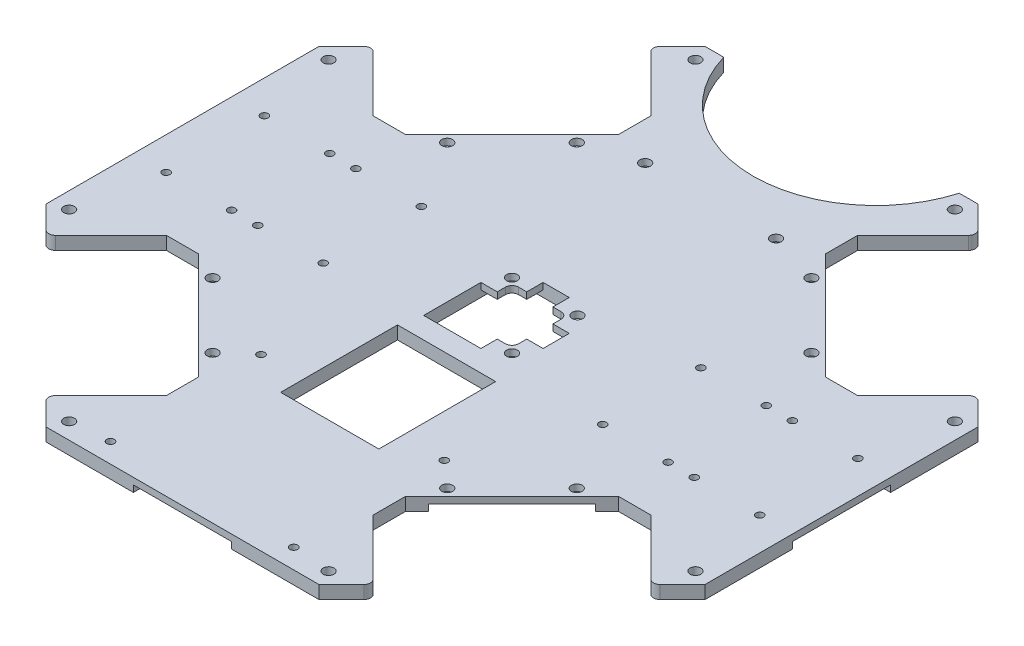
SolidWorks part; units mm, degrees
ref_plane "Front Plane" through (0, 0, 0) normal (0, 0, 1) x (1, 0, 0)
ref_plane "Top Plane" through (0, 0, 0) normal (0, 1, 0) x (1, 0, 0)
ref_plane "Right Plane" through (0, 0, 0) normal (1, 0, 0) x (0, 0, -1)
sketch "Sketch1" plane through (0, 0, 0) normal (0, 1, 0) x (1, 0, 0)
  line L1 (-41.7125, 100.7029) -> (-100.7029, 41.7125)
  line L2 (-100.7029, 41.7125) -> (-100.7029, -41.7125)
  line L3 (-100.7029, -41.7125) -> (-41.7125, -100.7029)
  line L4 (-41.7125, -100.7029) -> (41.7125, -100.7029)
  line L5 (41.7125, -100.7029) -> (100.7029, -41.7125)
  line L6 (100.7029, -41.7125) -> (100.7029, 41.7125)
  line L7 (100.7029, 41.7125) -> (41.7125, 100.7029)
  line L8 (41.7125, 100.7029) -> (-41.7125, 100.7029)
  circle A0 centre (0, 0) radius 100.7029 construction
  circle A1 centre (0, 0) radius 109 construction
  dimension "D1" = 218
extrude "Boss-Extrude1" add sketch "Sketch1" along normal blind 4
sketch "Sketch2" plane through (0, 4, 0) normal (0, 1, 0) x (1, 0, 0)
  line L5 (-92.4209, 49.9945) -> (-49.9945, 92.4209)
  line L6 (-92.4209, 49.9945) -> (-69.0864, 26.66)
  line L7 (-49.9945, 92.4209) -> (-26.66, 69.0864)
  line L8 (-69.0864, 26.66) -> (-26.66, 69.0864)
  line L9 (-41.7125, 100.7029) -> (-100.7029, 41.7125) construction
  line L10 (0, 0) -> (-71.2077, 71.2077) construction
  line L11 (100.7029, 41.7125) -> (41.7125, 100.7029) construction
  line L12 (49.9945, 92.4209) -> (92.4209, 49.9945)
  line L13 (49.9945, 92.4209) -> (26.66, 69.0864)
  line L14 (26.66, 69.0864) -> (69.0864, 26.66)
  line L15 (92.4209, 49.9945) -> (69.0864, 26.66)
  line L16 (92.4209, -49.9945) -> (49.9945, -92.4209)
  line L17 (92.4209, -49.9945) -> (69.0864, -26.66)
  line L18 (69.0864, -26.66) -> (26.66, -69.0864)
  line L19 (49.9945, -92.4209) -> (26.66, -69.0864)
  line L20 (-49.9945, -92.4209) -> (-92.4209, -49.9945)
  line L21 (-49.9945, -92.4209) -> (-26.66, -69.0864)
  line L22 (-26.66, -69.0864) -> (-69.0864, -26.66)
  line L23 (-92.4209, -49.9945) -> (-69.0864, -26.66)
  circle A0 centre (-55.6513, 35.8523) radius 1.65
  circle A1 centre (-35.8523, 55.6513) radius 1.65
  circle A2 centre (55.6513, 35.8523) radius 1.65
  circle A3 centre (35.8523, 55.6513) radius 1.65
  circle A4 centre (35.8523, -55.6513) radius 1.65
  circle A5 centre (55.6513, -35.8523) radius 1.65
  circle A6 centre (-55.6513, -35.8523) radius 1.65
  circle A7 centre (-35.8523, -55.6513) radius 1.65
  point P42 (0, 0)
  dimension "D7" = 3.3
  dimension "D8" = 3.3
  dimension "D1" = 60
  dimension "D2" = 33
  dimension "D3" = 3
  dimension "D4" = 3
  dimension "D5" = 28
  dimension "D6" = 14
  dimension "D10" = 71.7047
  dimension "D11" = 67.7029
  dimension "D9" = 4
extrude "Cut-Extrude1" cut sketch "Sketch2" against normal up to next
sketch "Sketch3" plane through (0, 4, 0) normal (0, 1, 0) x (1, 0, 0)
  line L0 (0, 0) -> (0, 50000) construction
  line L1 (-1015.9137, 73.7029) -> (48984.0863, 73.7029) construction
  line L2 (41.7125, 100.7029) -> (-41.7125, 100.7029) construction
  circle A0 centre (0, 111.2029) radius 37.5
  dimension "D1" = 75
  dimension "D2" = 27
extrude "Cut-Extrude2" cut sketch "Sketch3" against normal up to next
chamfer "Chamfer2" distance 7 angle 45 8 edges at (-69.0864, 2, 26.66) (-26.66, 2, 69.0864) (26.66, 2, 69.0864) (69.0864, 2, 26.66) (69.0864, 2, -26.66) (26.66, 2, -69.0864) (-69.0864, 2, -26.66) (-26.66, 2, -69.0864)
sketch "Sketch4" plane through (0, 4, 0) normal (0, 1, 0) x (1, 0, 0)
  line L0 (-36, 100.7029) -> (-41.7125, 100.7029) construction
  line L1 (-41.7125, 100.7029) -> (-49.9945, 92.4209) construction
  line L2 (41.7125, 100.7029) -> (36, 100.7029) construction
  line L3 (49.9945, 92.4209) -> (41.7125, 100.7029) construction
  circle A0 centre (-39.6414, 95.7029) radius 1.65
  circle A1 centre (39.6414, 95.7029) radius 1.65
  circle A2 centre (95.7029, 39.6414) radius 1.65
  circle A3 centre (95.7029, -39.6414) radius 1.65
  circle A4 centre (39.6414, -95.7029) radius 1.65
  circle A5 centre (-39.6414, -95.7029) radius 1.65
  circle A6 centre (-95.7029, -39.6414) radius 1.65
  circle A7 centre (-95.7029, 39.6414) radius 1.65
  point P22 (0, 0)
  dimension "D3" = 3.3
  dimension "D1" = 5
  dimension "D2" = 5
  dimension "D5" = 5
  dimension "D6" = 5
  dimension "D4" = 8
extrude "Cut-Extrude3" cut sketch "Sketch4" against normal up to next
sketch "Sketch5" plane through (0, 4, 0) normal (0, 1, 0) x (1, 0, 0)
  line L0 (-1000, 0) -> (49000, 0) construction
  line L1 (0, -1000) -> (0, 49000) construction
  line L2 (-62.7029, 15) -> (-42.7029, 15) construction
  line L3 (-90.7029, 15) -> (-70.7029, 15) construction
  line L4 (-90.7029, 15) -> (-90.7029, -15) construction
  line L5 (-90.7029, -15) -> (-70.7029, -15) construction
  line L6 (-70.7029, 15) -> (-70.7029, -15) construction
  line L7 (-62.7029, 15) -> (-62.7029, -15) construction
  line L8 (-62.7029, -15) -> (-42.7029, -15) construction
  line L9 (-42.7029, 15) -> (-42.7029, -15) construction
  line L10 (-100.7029, 41.7125) -> (-100.7029, -41.7125) construction
  line L11 (42.7029, 15) -> (42.7029, -15) construction
  line L12 (62.7029, -15) -> (42.7029, -15) construction
  line L13 (62.7029, 15) -> (62.7029, -15) construction
  line L14 (70.7029, 15) -> (70.7029, -15) construction
  line L15 (90.7029, -15) -> (70.7029, -15) construction
  line L16 (90.7029, 15) -> (90.7029, -15) construction
  line L17 (90.7029, 15) -> (70.7029, 15) construction
  line L18 (62.7029, 15) -> (42.7029, 15) construction
  circle A0 centre (-90.7029, 15) radius 1.15
  circle A1 centre (-70.7029, 15) radius 1.15
  circle A2 centre (-62.7029, 15) radius 1.15
  circle A3 centre (-42.7029, 15) radius 1.15
  circle A4 centre (-42.7029, -15) radius 1.15
  circle A5 centre (-62.7029, -15) radius 1.15
  circle A6 centre (-70.7029, -15) radius 1.15
  circle A7 centre (-90.7029, -15) radius 1.15
  circle A8 centre (90.7029, -15) radius 1.15
  circle A9 centre (70.7029, -15) radius 1.15
  circle A10 centre (62.7029, -15) radius 1.15
  circle A11 centre (42.7029, -15) radius 1.15
  circle A12 centre (42.7029, 15) radius 1.15
  circle A13 centre (62.7029, 15) radius 1.15
  circle A14 centre (70.7029, 15) radius 1.15
  circle A15 centre (90.7029, 15) radius 1.15
  dimension "D9" = 2.3
  dimension "D10" = 2.3
  dimension "D11" = 2.3
  dimension "D12" = 2.3
  dimension "D13" = 2.3
  dimension "D14" = 2.3
  dimension "D15" = 2.3
  dimension "D16" = 2.3
  dimension "D1" = 20
  dimension "D2" = 30
  dimension "D3" = 15
  dimension "D4" = 20
  dimension "D5" = 30
  dimension "D6" = 15
  dimension "D7" = 8
  dimension "D8" = 10
extrude "Cut-Extrude4" cut sketch "Sketch5" against normal up to next
sketch "Sketch6" plane through (0, 0, 0) normal (0, -1, 0) x (1, 0, 0)
  line L0 (0, -1000) -> (0, 49000) construction
  line L1 (-89.4616, 17.15) -> (-91.9442, 17.15)
  line L2 (-91.9442, 17.15) -> (-93.1855, 15)
  line L3 (-93.1855, 15) -> (-91.9442, 12.85)
  line L4 (-91.9442, 12.85) -> (-89.4616, 12.85)
  line L5 (-89.4616, 12.85) -> (-88.2203, 15)
  line L6 (-88.2203, 15) -> (-89.4616, 17.15)
  line L7 (-73.1855, 15) -> (-71.9442, 12.85)
  line L8 (-71.9442, 12.85) -> (-69.4616, 12.85)
  line L9 (-69.4616, 12.85) -> (-68.2203, 15)
  line L10 (-68.2203, 15) -> (-69.4616, 17.15)
  line L11 (-69.4616, 17.15) -> (-71.9442, 17.15)
  line L12 (-71.9442, 17.15) -> (-73.1855, 15)
  line L13 (-63.9442, 17.15) -> (-65.1855, 15)
  line L14 (-65.1855, 15) -> (-63.9442, 12.85)
  line L15 (-63.9442, 12.85) -> (-61.4616, 12.85)
  line L16 (-61.4616, 12.85) -> (-60.2203, 15)
  line L17 (-60.2203, 15) -> (-61.4616, 17.15)
  line L18 (-61.4616, 17.15) -> (-63.9442, 17.15)
  line L19 (-43.9442, 17.15) -> (-45.1855, 15)
  line L20 (-45.1855, 15) -> (-43.9442, 12.85)
  line L21 (-43.9442, 12.85) -> (-41.4616, 12.85)
  line L22 (-41.4616, 12.85) -> (-40.2203, 15)
  line L23 (-40.2203, 15) -> (-41.4616, 17.15)
  line L24 (-41.4616, 17.15) -> (-43.9442, 17.15)
  line L25 (-91.9442, -12.85) -> (-93.1855, -15)
  line L26 (-93.1855, -15) -> (-91.9442, -17.15)
  line L27 (-91.9442, -17.15) -> (-89.4616, -17.15)
  line L28 (-89.4616, -17.15) -> (-88.2203, -15)
  line L29 (-88.2203, -15) -> (-89.4616, -12.85)
  line L30 (-89.4616, -12.85) -> (-91.9442, -12.85)
  line L31 (-73.1855, -15) -> (-71.9442, -17.15)
  line L32 (-71.9442, -17.15) -> (-69.4616, -17.15)
  line L33 (-69.4616, -17.15) -> (-68.2203, -15)
  line L34 (-68.2203, -15) -> (-69.4616, -12.85)
  line L35 (-69.4616, -12.85) -> (-71.9442, -12.85)
  line L36 (-71.9442, -12.85) -> (-73.1855, -15)
  line L37 (-63.9442, -12.85) -> (-65.1855, -15)
  line L38 (-65.1855, -15) -> (-63.9442, -17.15)
  line L39 (-63.9442, -17.15) -> (-61.4616, -17.15)
  line L40 (-61.4616, -17.15) -> (-60.2203, -15)
  line L41 (-60.2203, -15) -> (-61.4616, -12.85)
  line L42 (-61.4616, -12.85) -> (-63.9442, -12.85)
  line L43 (-43.9442, -12.85) -> (-45.1855, -15)
  line L44 (-45.1855, -15) -> (-43.9442, -17.15)
  line L45 (-43.9442, -17.15) -> (-41.4616, -17.15)
  line L46 (-41.4616, -17.15) -> (-40.2203, -15)
  line L47 (-40.2203, -15) -> (-41.4616, -12.85)
  line L48 (-41.4616, -12.85) -> (-43.9442, -12.85)
  line L49 (41.4616, -12.85) -> (43.9442, -12.85)
  line L50 (40.2203, -15) -> (41.4616, -12.85)
  line L51 (41.4616, -17.15) -> (40.2203, -15)
  line L52 (43.9442, -17.15) -> (41.4616, -17.15)
  line L53 (45.1855, -15) -> (43.9442, -17.15)
  line L54 (43.9442, -12.85) -> (45.1855, -15)
  line L55 (61.4616, -12.85) -> (63.9442, -12.85)
  line L56 (60.2203, -15) -> (61.4616, -12.85)
  line L57 (61.4616, -17.15) -> (60.2203, -15)
  line L58 (63.9442, -17.15) -> (61.4616, -17.15)
  line L59 (65.1855, -15) -> (63.9442, -17.15)
  line L60 (63.9442, -12.85) -> (65.1855, -15)
  line L61 (71.9442, -12.85) -> (73.1855, -15)
  line L62 (69.4616, -12.85) -> (71.9442, -12.85)
  line L63 (68.2203, -15) -> (69.4616, -12.85)
  line L64 (69.4616, -17.15) -> (68.2203, -15)
  line L65 (71.9442, -17.15) -> (69.4616, -17.15)
  line L66 (73.1855, -15) -> (71.9442, -17.15)
  line L67 (89.4616, -12.85) -> (91.9442, -12.85)
  line L68 (88.2203, -15) -> (89.4616, -12.85)
  line L69 (89.4616, -17.15) -> (88.2203, -15)
  line L70 (91.9442, -17.15) -> (89.4616, -17.15)
  line L71 (93.1855, -15) -> (91.9442, -17.15)
  line L72 (91.9442, -12.85) -> (93.1855, -15)
  line L73 (41.4616, 17.15) -> (43.9442, 17.15)
  line L74 (40.2203, 15) -> (41.4616, 17.15)
  line L75 (41.4616, 12.85) -> (40.2203, 15)
  line L76 (43.9442, 12.85) -> (41.4616, 12.85)
  line L77 (45.1855, 15) -> (43.9442, 12.85)
  line L78 (43.9442, 17.15) -> (45.1855, 15)
  line L79 (61.4616, 17.15) -> (63.9442, 17.15)
  line L80 (60.2203, 15) -> (61.4616, 17.15)
  line L81 (61.4616, 12.85) -> (60.2203, 15)
  line L82 (63.9442, 12.85) -> (61.4616, 12.85)
  line L83 (65.1855, 15) -> (63.9442, 12.85)
  line L84 (63.9442, 17.15) -> (65.1855, 15)
  line L85 (71.9442, 17.15) -> (73.1855, 15)
  line L86 (69.4616, 17.15) -> (71.9442, 17.15)
  line L87 (68.2203, 15) -> (69.4616, 17.15)
  line L88 (69.4616, 12.85) -> (68.2203, 15)
  line L89 (71.9442, 12.85) -> (69.4616, 12.85)
  line L90 (73.1855, 15) -> (71.9442, 12.85)
  line L91 (88.2203, 15) -> (89.4616, 17.15)
  line L92 (89.4616, 12.85) -> (88.2203, 15)
  line L93 (91.9442, 12.85) -> (89.4616, 12.85)
  line L94 (93.1855, 15) -> (91.9442, 12.85)
  line L95 (91.9442, 17.15) -> (93.1855, 15)
  line L96 (89.4616, 17.15) -> (91.9442, 17.15)
  circle A0 centre (-90.7029, 15) radius 2.15 construction
  circle A1 centre (-70.7029, 15) radius 2.15 construction
  circle A2 centre (-62.7029, 15) radius 2.15 construction
  circle A3 centre (-42.7029, 15) radius 2.15 construction
  circle A4 centre (-90.7029, -15) radius 2.15 construction
  circle A5 centre (-70.7029, -15) radius 2.15 construction
  circle A6 centre (-62.7029, -15) radius 2.15 construction
  circle A7 centre (-42.7029, -15) radius 2.15 construction
  circle A8 centre (42.7029, -15) radius 2.15 construction
  circle A9 centre (62.7029, -15) radius 2.15 construction
  circle A10 centre (70.7029, -15) radius 2.15 construction
  circle A11 centre (90.7029, -15) radius 2.15 construction
  circle A12 centre (42.7029, 15) radius 2.15 construction
  circle A13 centre (62.7029, 15) radius 2.15 construction
  circle A14 centre (70.7029, 15) radius 2.15 construction
  circle A15 centre (90.7029, 15) radius 2.15 construction
  point P64 (-92.5648, -16.075)
  dimension "D1" = 4.3
  dimension "D2" = 4.3
  dimension "D3" = 4.3
  dimension "D4" = 4.3
  dimension "D5" = 4.3
  dimension "D6" = 4.3
  dimension "D7" = 4.3
  dimension "D8" = 4.3
extrude "Cut-Extrude5" cut sketch "Sketch6" against normal blind 2
sketch "Sketch7" plane through (0, 0, 0) normal (0, -1, 0) x (1, 0, 0)
  line L0 (-60.6011, -35.1452) -> (-54.9442, -40.8021)
  line L1 (-60.6011, -35.1452) -> (-50.7016, -25.2457)
  line L2 (-54.9442, -40.8021) -> (-45.0447, -30.9026)
  line L3 (-50.7016, -25.2457) -> (-45.0447, -30.9026)
  line L4 (-31.6097, -64.1366) -> (-64.1366, -31.6097) construction
  line L5 (-47.8732, -47.8732) -> (0, 0) construction
  line L6 (-40.8021, -54.9442) -> (-30.9026, -45.0447)
  line L7 (-25.2457, -50.7016) -> (-30.9026, -45.0447)
  line L8 (-35.1452, -60.6011) -> (-25.2457, -50.7016)
  line L9 (-35.1452, -60.6011) -> (-40.8021, -54.9442)
  line L10 (-35.1452, 60.6011) -> (-40.8021, 54.9442)
  line L11 (-35.1452, 60.6011) -> (-25.2457, 50.7016)
  line L12 (-25.2457, 50.7016) -> (-30.9026, 45.0447)
  line L13 (-40.8021, 54.9442) -> (-30.9026, 45.0447)
  line L14 (-54.9442, 40.8021) -> (-45.0447, 30.9026)
  line L15 (-50.7016, 25.2457) -> (-45.0447, 30.9026)
  line L16 (-60.6011, 35.1452) -> (-50.7016, 25.2457)
  line L17 (-60.6011, 35.1452) -> (-54.9442, 40.8021)
  line L18 (60.6011, 35.1452) -> (54.9442, 40.8021)
  line L19 (60.6011, 35.1452) -> (50.7016, 25.2457)
  line L20 (50.7016, 25.2457) -> (45.0447, 30.9026)
  line L21 (54.9442, 40.8021) -> (45.0447, 30.9026)
  line L22 (40.8021, 54.9442) -> (30.9026, 45.0447)
  line L23 (25.2457, 50.7016) -> (30.9026, 45.0447)
  line L24 (35.1452, 60.6011) -> (25.2457, 50.7016)
  line L25 (35.1452, 60.6011) -> (40.8021, 54.9442)
  line L26 (35.1452, -60.6011) -> (40.8021, -54.9442)
  line L27 (35.1452, -60.6011) -> (25.2457, -50.7016)
  line L28 (25.2457, -50.7016) -> (30.9026, -45.0447)
  line L29 (40.8021, -54.9442) -> (30.9026, -45.0447)
  line L30 (54.9442, -40.8021) -> (45.0447, -30.9026)
  line L31 (50.7016, -25.2457) -> (45.0447, -30.9026)
  line L32 (60.6011, -35.1452) -> (50.7016, -25.2457)
  line L33 (60.6011, -35.1452) -> (54.9442, -40.8021)
  circle A0 centre (-55.6513, -35.8523) radius 1.65 construction
  circle A1 centre (55.6513, -35.8523) radius 1.65 construction
  point P42 (0, 0)
  dimension "D1" = 14
  dimension "D2" = 8
  dimension "D3" = 4
  dimension "D5" = 53.7029
  dimension "D6" = 4
  dimension "D4" = 4
extrude "Cut-Extrude6" cut sketch "Sketch7" against normal blind 2
sketch "Sketch8" plane through (0, 4, 0) normal (0, 1, 0) x (1, 0, 0)
  line L1 (-10, -10) -> (10, -10) construction
  line L2 (-10, -10) -> (-10, 10) construction
  line L3 (-10, 10) -> (10, 10) construction
  line L4 (10, -10) -> (10, 10) construction
  line L5 (-6.5, 8.5) -> (6.5, 8.5)
  line L6 (-8.5, 6.5) -> (-8.5, -6.5)
  line L7 (-6.5, -8.5) -> (6.5, -8.5)
  line L8 (8.5, 6.5) -> (8.5, -6.5)
  circle A0 centre (-10, -10) radius 1.65
  circle A1 centre (10, -10) radius 1.65
  circle A2 centre (10, 10) radius 1.65
  circle A3 centre (-10, 10) radius 1.65
  arc A4 (-8.5, -6.5) -> (-6.5, -8.5) centre (-6.5, -6.5) ccw
  arc A5 (6.5, -8.5) -> (8.5, -6.5) centre (6.5, -6.5) ccw
  arc A6 (6.5, 8.5) -> (8.5, 6.5) centre (6.5, 6.5) cw
  arc A7 (-6.5, 8.5) -> (-8.5, 6.5) centre (-6.5, 6.5) ccw
  dimension "D5" = 3.3
  dimension "D6" = 3.3
  dimension "D7" = 3.3
  dimension "D8" = 3.3
  dimension "D13" = 2
  dimension "D1" = 20
  dimension "D2" = 20
  dimension "D3" = 10
  dimension "D4" = 10
  dimension "D9" = 3
  dimension "D10" = 3
  dimension "D11" = 3
  dimension "D12" = 3
extrude "Cut-Extrude7" cut sketch "Sketch8" against normal up to next
sketch "Sketch10" plane through (0, 0, 0) normal (0, -1, 0) x (1, 0, 0)
  line L0 (6.5, 8.5) -> (-6.5, 8.5) construction
  line L1 (-4, 8.5) -> (4, 8.5)
  line L2 (-4, 8.5) -> (-4, 13.5)
  line L3 (-4, 13.5) -> (4, 13.5)
  line L4 (4, 8.5) -> (4, 13.5)
  line L5 (8.5, 4) -> (13.5, 4)
  line L6 (8.5, 4) -> (8.5, -4)
  line L7 (8.5, -4) -> (13.5, -4)
  line L8 (13.5, 4) -> (13.5, -4)
  line L9 (4, -8.5) -> (4, -13.5)
  line L10 (4, -8.5) -> (-4, -8.5)
  line L11 (-4, -8.5) -> (-4, -13.5)
  line L12 (4, -13.5) -> (-4, -13.5)
  line L13 (-8.5, -4) -> (-13.5, -4)
  line L14 (-8.5, -4) -> (-8.5, 4)
  line L15 (-8.5, 4) -> (-13.5, 4)
  line L16 (-13.5, -4) -> (-13.5, 4)
  point P6 (0, 8.5)
  point P23 (0, 0)
  dimension "D1" = 8
  dimension "D2" = 5
  dimension "D4" = 4
  dimension "D5" = 8.5
  dimension "D3" = 4
extrude "Cut-Extrude9" cut sketch "Sketch10" against normal up to next
sketch "Sketch11" plane through (0, 0, 0) normal (0, -1, 0) x (1, 0, 0)
  line L0 (-1000, -73.7029) -> (49000, -73.7029) construction
  circle A0 centre (-20, -60.7029) radius 1.65
  circle A1 centre (20, -60.7029) radius 1.65
  arc A2 (36, -100.7029) -> (-36, -100.7029) centre (0, -111.2029) ccw construction
  point P10 (0, -73.7029)
  dimension "D5" = 3.3
  dimension "D6" = 3.3
  dimension "D1" = 13
  dimension "D2" = 13
  dimension "D3" = 40
  dimension "D4" = 20
extrude "Cut-Extrude10" cut sketch "Sketch11" against normal up to next
sketch "Sketch12" plane through (0, 4, 0) normal (0, 1, 0) x (1, 0, 0)
  line L0 (-41.7125, -100.7029) -> (41.7125, -100.7029) construction
  line L1 (-15, -20) -> (15, -20)
  line L2 (-15, -20) -> (-15, -55.7029)
  line L3 (-15, -55.7029) -> (15, -55.7029)
  line L4 (15, -20) -> (15, -55.7029)
  dimension "D1" = 30
  dimension "D2" = 15
  dimension "D3" = 45
  dimension "D4" = 20
extrude "Cut-Extrude11" cut sketch "Sketch12" against normal up to next
sketch "Sketch13" plane through (0, 0, 0) normal (0, -1, 0) x (-1, 0, 0)
  line L0 (100.7029, 41.7125) -> (100.7029, -41.7125) construction
  line L1 (15, 76.8336) -> (-15, 76.8336)
  line L2 (15, 76.8336) -> (15, 36.8336)
  line L3 (15, 36.8336) -> (-15, 36.8336)
  line L4 (-15, 76.8336) -> (-15, 36.8336)
  line L5 (15, 76.8336) -> (-15, 36.8336) construction
  line L6 (15, 36.8336) -> (-15, 76.8336) construction
  line L7 (100.7029, 15) -> (50.7029, 15)
  line L8 (100.7029, 15) -> (100.7029, -15)
  line L9 (100.7029, -15) -> (50.7029, -15)
  line L10 (50.7029, 15) -> (50.7029, -15)
  line L11 (100.7029, 15) -> (50.7029, -15) construction
  line L12 (100.7029, -15) -> (50.7029, 15) construction
  line L13 (0, 2.2) -> (0, -2.2) construction
  line L14 (-100.7029, -15) -> (-50.7029, 15) construction
  line L15 (-100.7029, 15) -> (-50.7029, -15) construction
  line L16 (-50.7029, 15) -> (-50.7029, -15)
  line L17 (-100.7029, -15) -> (-50.7029, -15)
  line L18 (-100.7029, 15) -> (-100.7029, -15)
  line L19 (-100.7029, 15) -> (-50.7029, 15)
  line L20 (-15, -55.7029) -> (15, -55.7029) construction
  line L21 (15, -100.7029) -> (-15, -100.7029)
  line L22 (15, -100.7029) -> (15, -55.7029)
  line L23 (15, -55.7029) -> (-15, -55.7029)
  line L24 (-15, -100.7029) -> (-15, -55.7029)
  line L25 (15, -100.7029) -> (-15, -55.7029) construction
  line L26 (15, -55.7029) -> (-15, -100.7029) construction
  line L27 (41.7125, -100.7029) -> (-41.7125, -100.7029) construction
  arc A0 (-36, 100.7029) -> (36, 100.7029) centre (0, 111.2029) ccw construction
  point P0 (0, 56.8336)
  point P10 (75.7029, 0)
  point P23 (-75.7029, 0)
  point P24 (0, -78.2029)
  dimension "D1" = 40
  dimension "D2" = 30
  dimension "D3" = 30
  dimension "D4" = 50
extrude "Cut-Extrude12" cut sketch "Sketch13" against normal offset from surface 2 up to face at (0, 4, 37.8514)
sketch "Sketch15" plane through (0, 0, 0) normal (0, -1, 0) x (1, 0, 0)
  circle A0 centre (-20, -60.7029) radius 4
  circle A1 centre (20, -60.7029) radius 4
  dimension "D1" = 8
  dimension "D2" = 8
extrude "Cut-Extrude13" cut sketch "Sketch15" against normal blind 2
sketch "Sketch16" plane through (0, 4, 0) normal (0, 1, 0) x (1, 0, 0)
  line L0 (-41.7125, -100.7029) -> (41.7125, -100.7029) construction
  line L1 (-28, -94.7029) -> (28, -94.7029) construction
  line L2 (-28, -94.7029) -> (-28, -48.7029) construction
  line L3 (-28, -48.7029) -> (28, -48.7029) construction
  line L4 (28, -94.7029) -> (28, -48.7029) construction
  line L5 (-28, -94.7029) -> (28, -48.7029) construction
  line L6 (-28, -48.7029) -> (28, -94.7029) construction
  circle A0 centre (-28, -48.7029) radius 1.15
  circle A1 centre (28, -48.7029) radius 1.15
  circle A2 centre (28, -94.7029) radius 1.15
  circle A3 centre (-28, -94.7029) radius 1.15
  point P0 (0, -71.7029)
  dimension "D4" = 2.3
  dimension "D5" = 2.3
  dimension "D6" = 2.3
  dimension "D7" = 2.3
  dimension "D1" = 56
  dimension "D2" = 46
  dimension "D3" = 6
extrude "Cut-Extrude14" cut sketch "Sketch16" against normal up to next
sketch "Sketch17" plane through (0, 0, 0) normal (0, -1, 0) x (1, 0, 0)
  circle A0 centre (-28, 94.7029) radius 2.5
  circle A1 centre (28, 94.7029) radius 2.5
  circle A2 centre (28, 48.7029) radius 2.5
  circle A3 centre (-28, 48.7029) radius 2.5
  dimension "D1" = 5
  dimension "D2" = 5
  dimension "D3" = 5
  dimension "D4" = 5
extrude "Cut-Extrude16" cut sketch "Sketch17" against normal up to surface (2 mm away) up to face at (-31.4218, 2, 51.5221)
sketch "Sketch18" plane through (0, 0, 0) normal (0, -1, 0) x (-1, 0, 0)
  line L0 (-4, -13.5) -> (4, -13.5) construction
  line L1 (13.5, 13.5) -> (-13.5, 13.5)
  line L2 (13.5, 13.5) -> (13.5, -13.5)
  line L3 (13.5, -13.5) -> (-13.5, -13.5)
  line L4 (-13.5, 13.5) -> (-13.5, -13.5)
  line L5 (13.5, 13.5) -> (-13.5, -13.5) construction
  line L6 (13.5, -13.5) -> (-13.5, 13.5) construction
  line L7 (13.5, -4) -> (13.5, 4) construction
  point P0 (0, 0)
extrude "Cut-Extrude17" cut sketch "Sketch18" against normal blind 2
sketch "Sketch19" plane through (0, 2, 0) normal (0, -1, 0) x (1, 0, 0)
  line L5 (-13.5, 4) -> (-4, 4)
  line L6 (-13.5, 4) -> (-13.5, 13.5)
  line L7 (-13.5, 13.5) -> (-4, 13.5)
  line L8 (-4, 4) -> (-4, 13.5)
extrude "Cut-Extrude19" cut sketch "Sketch19" against normal up to next
sketch "Sketch20" plane through (0, 0, 0) normal (0, -1, 0) x (1, 0, 0)
  line L0 (-54.9442, 40.8021) -> (-33.731, 19.5889)
  line L1 (-33.731, 19.5889) -> (-19.5889, 33.731)
  line L2 (-19.5889, 33.731) -> (-40.8021, 54.9442)
  line L3 (-40.8021, 54.9442) -> (-54.9442, 40.8021)
  line L4 (-40.8021, 54.9442) -> (-30.9026, 45.0447) construction
  line L5 (40.8021, 54.9442) -> (19.5889, 33.731)
  line L6 (19.5889, 33.731) -> (33.731, 19.5889)
  line L7 (33.731, 19.5889) -> (54.9442, 40.8021)
  line L8 (54.9442, 40.8021) -> (40.8021, 54.9442)
  line L9 (54.9442, -40.8021) -> (33.731, -19.5889)
  line L10 (33.731, -19.5889) -> (19.5889, -33.731)
  line L11 (19.5889, -33.731) -> (40.8021, -54.9442)
  line L12 (40.8021, -54.9442) -> (54.9442, -40.8021)
  line L13 (-40.8021, -54.9442) -> (-19.5889, -33.731)
  line L14 (-19.5889, -33.731) -> (-33.731, -19.5889)
  line L15 (-33.731, -19.5889) -> (-54.9442, -40.8021)
  line L16 (-54.9442, -40.8021) -> (-40.8021, -54.9442)
  point P23 (0, 0)
  dimension "D1" = 30
  dimension "D2" = 4
extrude "Cut-Extrude20" cut sketch "Sketch20" against normal up to surface (2 mm away) up to face at (-52.8229, 2, 33.0239)
fillet "Fillet1" radius 2 8 edges at (-92.4209, 2, -49.9945) (-49.9945, 2, -92.4209) (49.9945, 2, -92.4209) (92.4209, 2, -49.9945) (92.4209, 2, 49.9945) (49.9945, 2, 92.4209) (-92.4209, 2, 49.9945) (-49.9945, 2, 92.4209)
